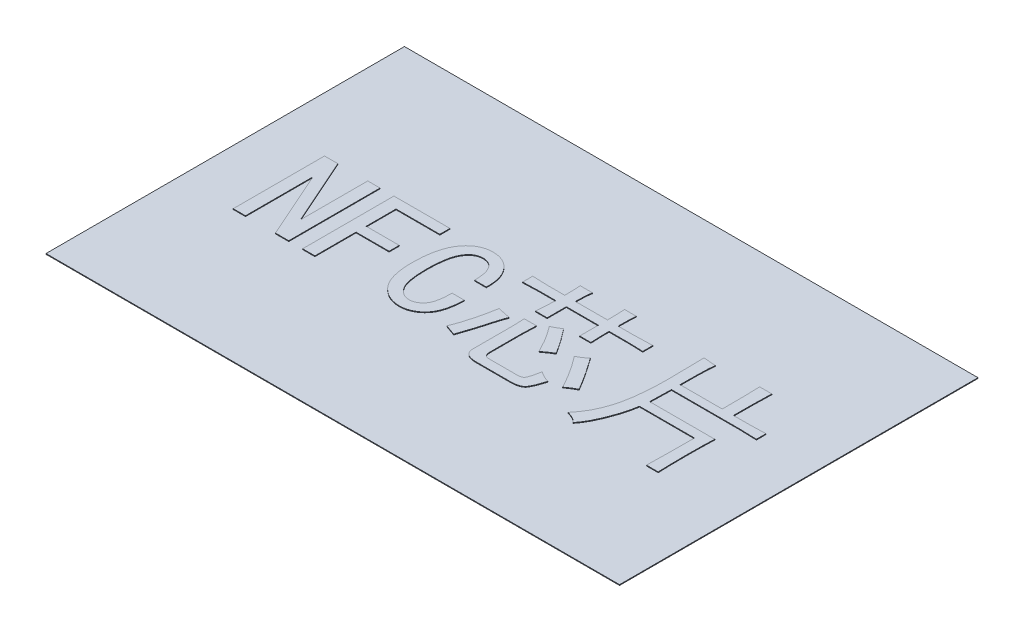
SolidWorks part; units mm, degrees
ref_plane "前视基准面" through (0, 0, 0) normal (0, 0, 1) x (1, 0, 0)
ref_plane "上视基准面" through (0, 0, 0) normal (0, 1, 0) x (1, 0, 0)
ref_plane "右视基准面" through (0, 0, 0) normal (1, 0, 0) x (0, 0, -1)
sketch "草图1" plane through (0, 0, 0) normal (0, 1, 0) x (1, 0, 0)
  line L1 (0, 0) -> (80, 0)
  line L2 (0, 0) -> (0, -50)
  line L3 (0, -50) -> (80, -50)
  line L4 (80, 0) -> (80, -50)
  dimension "D1" = 80
  dimension "D2" = 50
extrude "凸台-拉伸1" add sketch "草图1" along normal blind 0.1
sketch "草图2" plane through (0, 0.1, 0) normal (0, 1, 0) x (1, 0, 0)
  line L0 (0, 0) -> (0, -50) construction
  line L1 (0, -50) -> (80, -50) construction
  text T0 "NFC芯片" font "黑体" height in points 42
  dimension "D1" = 7
  dimension "D2" = 18
extrude "凸台-拉伸2" add sketch "草图2" along normal blind 0.1
